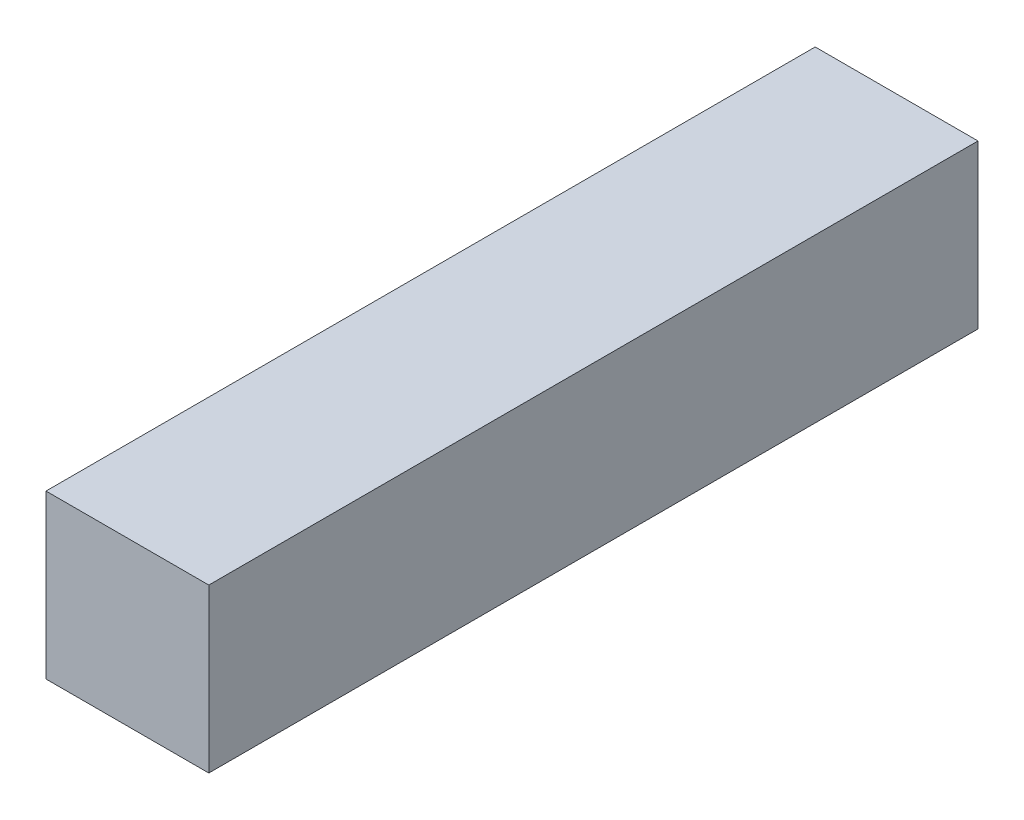
SolidWorks part; units mm, degrees
ref_plane "Alzado" through (0, 0, 0) normal (0, 0, 1) x (1, 0, 0)
ref_plane "Planta" through (0, 0, 0) normal (0, 1, 0) x (1, 0, 0)
ref_plane "Vista lateral" through (0, 0, 0) normal (1, 0, 0) x (0, 0, -1)
sketch "Croquis1" plane through (0, 0, 0) normal (0, 0, 1) x (1, 0, 0)
  line L1 (3.175, -3.175) -> (-3.175, -3.175)
  line L2 (3.175, -3.175) -> (3.175, 3.175)
  line L3 (3.175, 3.175) -> (-3.175, 3.175)
  line L4 (-3.175, -3.175) -> (-3.175, 3.175)
  line L5 (3.175, -3.175) -> (-3.175, 3.175) construction
  line L6 (3.175, 3.175) -> (-3.175, -3.175) construction
  point P0 (0, 0)
  dimension "D1" = 6.35
  dimension "D2" = 6.35
extrude "Saliente-Extruir1" add sketch "Croquis1" along normal blind 30
